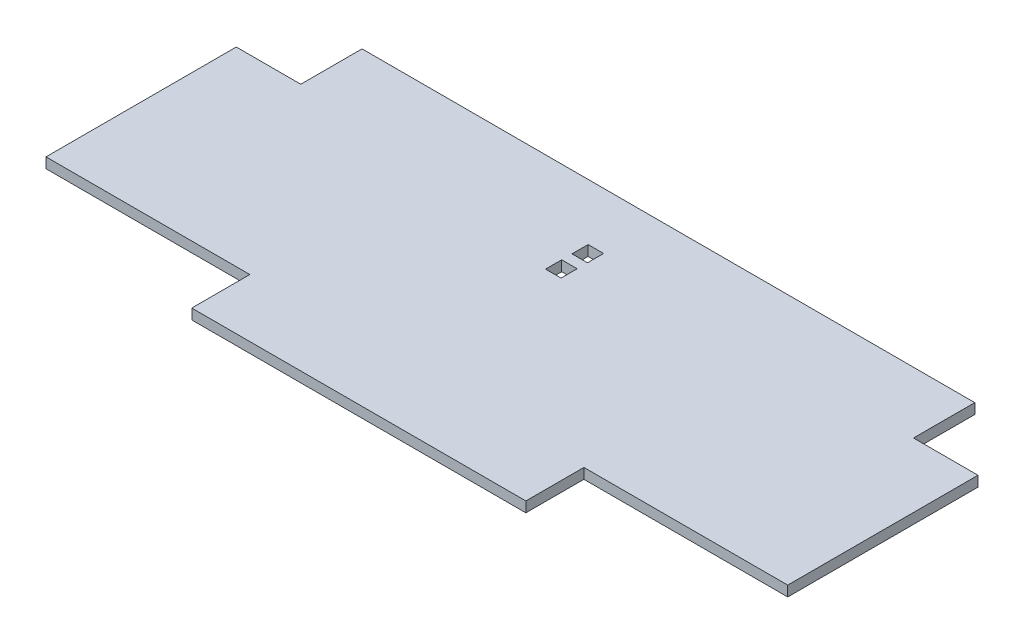
SolidWorks part; units mm, degrees
ref_plane "前视基准面" through (0, 0, 0) normal (0, 0, 1) x (1, 0, 0)
ref_plane "上视基准面" through (0, 0, 0) normal (0, 1, 0) x (1, 0, 0)
ref_plane "右视基准面" through (0, 0, 0) normal (1, 0, 0) x (0, 0, -1)
sketch "草图1" plane through (0, 0, 0) normal (0, 1, 0) x (1, 0, 0)
  line L0 (-115, 9) -> (-83.4, 9)
  line L1 (-83.4, 0) -> (-31.6, 0)
  line L3 (-83.4, 9) -> (-83.4, 0)
  line L4 (0, 9) -> (-31.6, 9)
  line L5 (-31.6, 9) -> (-31.6, 0)
  line L6 (-115, 38.5) -> (-105, 38.5)
  line L8 (-10, 48) -> (-10, 38.5)
  line L9 (-10, 38.5) -> (0, 38.5)
  line L10 (0, 38.5) -> (0, 9)
  line L11 (-105, 38.5) -> (-105, 48)
  line L12 (-105, 48) -> (-10, 48)
  line L13 (-115, 38.5) -> (-115, 9)
extrude "凸台-拉伸1" add sketch "草图1" along normal blind 1.6
sketch "草图2" plane through (0, 1.6, 0) normal (0, 1, 0) x (1, 0, 0)
  line L0 (-58.8, 36.75) -> (-58.8, 39.25)
  line L1 (-58.8, 39.25) -> (-61.2, 39.25)
  line L2 (-61.2, 35.15) -> (-61.2, 32.65)
  line L3 (-58.8, 32.65) -> (-61.2, 32.65)
  line L4 (-58.8, 32.65) -> (-58.8, 35.15)
  line L6 (-58.8, 36.75) -> (-61.2, 36.75)
  line L8 (-61.2, 35.15) -> (-58.8, 35.15)
  line L10 (-61.2, 36.75) -> (-61.2, 39.25)
extrude "切除-拉伸1" cut sketch "草图2" against normal blind 10
